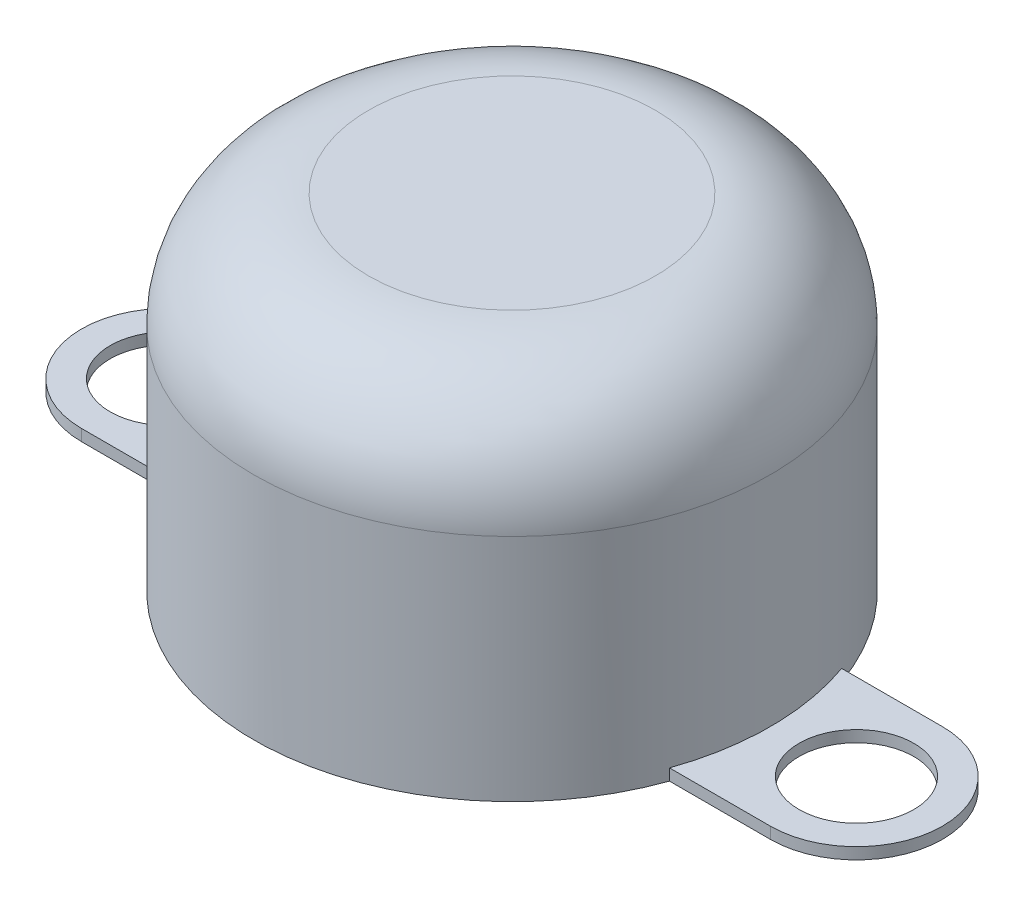
SolidWorks part; units mm, degrees
ref_plane "前视基准面" through (0, 0, 0) normal (0, 0, 1) x (1, 0, 0)
ref_plane "上视基准面" through (0, 0, 0) normal (0, 1, 0) x (1, 0, 0)
ref_plane "右视基准面" through (0, 0, 0) normal (1, 0, 0) x (0, 0, -1)
sketch "草图2" plane through (0, 0, 0) normal (0, 1, 0) x (1, 0, 0)
  circle A0 centre (0, 0) radius 22.5
  dimension "D1" = 45
extrude "凸台-拉伸1" add sketch "草图2" along normal blind 30
fillet "圆角1" radius 10 1 edges at (0, 30, 22.5)
sketch "草图3" plane through (0, 0, 0) normal (0, 1, 0) x (1, 0, 0)
  line L0 (-22.5, 0) -> (-30, 0)
  line L4 (-21.2132, 7.5) -> (-30, 7.5)
  line L5 (-21.2132, -7.5) -> (-30, -7.5)
  line L6 (0, 7.5) -> (-30, 7.5) construction
  line L7 (0, 0) -> (-30, 0) construction
  line L8 (0, -7.5) -> (-30, -7.5) construction
  arc A2 (-30, 7.5) -> (-30, -7.5) centre (-30, 0) ccw
  arc A3 (-21.2132, 7.5) -> (-21.2132, -7.5) centre (0, 0) ccw
  circle A4 centre (0, 0) radius 22.5 construction
  circle A5 centre (-30, 0) radius 5
  dimension "D1" = 30
  dimension "D4" = 7.5
  dimension "D5" = 7.5
shell "抽壳1" thickness 1
extrude "凸台-拉伸2" add sketch "草图3" along normal blind 1
mirror "镜向1" about plane through (0, 0, 0) normal (1, 0, 0) of "凸台-拉伸2"
